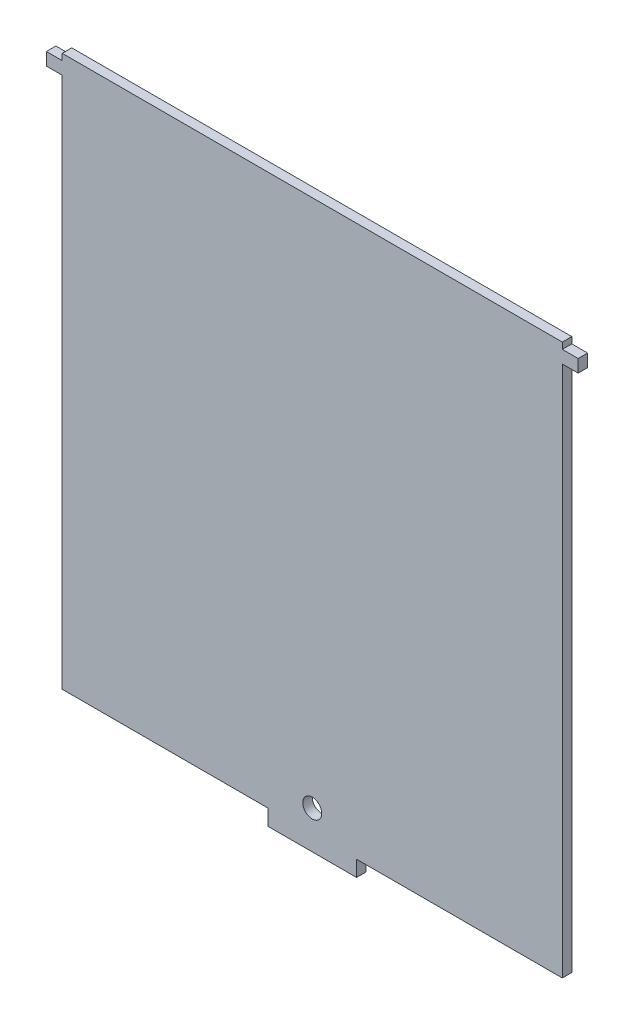
SolidWorks part; units mm, degrees
ref_plane "Front Plane" through (0, 0, 0) normal (0, 0, 1) x (1, 0, 0)
ref_plane "Top Plane" through (0, 0, 0) normal (0, 1, 0) x (1, 0, 0)
ref_plane "Right Plane" through (0, 0, 0) normal (1, 0, 0) x (0, 0, -1)
sketch "Sketch2" plane through (0, 0, 0) normal (0, 0, 1) x (1, 0, 0)
  line L0 (10.4351, -72.3206) -> (75.4351, -72.3206)
  line L2 (-82.5649, 95.6794) -> (-82.5649, -72.3206)
  line L3 (-82.5649, -72.3206) -> (-17.5649, -72.3206)
  line L4 (75.4351, 95.6794) -> (75.4351, -72.3206)
  line L5 (75.4351, 99.6794) -> (80.4351, 99.6794)
  line L7 (75.4351, 95.6794) -> (80.4351, 95.6794)
  line L8 (80.4351, 99.6794) -> (80.4351, 95.6794)
  line L9 (-82.5649, 99.6794) -> (-87.5649, 99.6794)
  line L11 (-82.5649, 95.6794) -> (-87.5649, 95.6794)
  line L12 (-87.5649, 99.6794) -> (-87.5649, 95.6794)
  line L14 (-17.5649, -72.3206) -> (-17.5649, -77.3206)
  line L15 (-17.5649, -77.3206) -> (10.4351, -77.3206)
  line L16 (10.4351, -72.3206) -> (10.4351, -77.3206)
  line L19 (-82.5649, 99.6794) -> (-82.5649, 101.6794)
  line L20 (-82.5649, 101.6794) -> (75.4351, 101.6794)
  line L21 (75.4351, 99.6794) -> (75.4351, 101.6794)
  circle A0 centre (-3.5649, -65.3206) radius 3
  dimension "D10" = 14
  dimension "D1" = 158
  dimension "D2" = 5
  dimension "D3" = 4
  dimension "D4" = 5
  dimension "D5" = 4
  dimension "D6" = 172
  dimension "D7" = 28
  dimension "D8" = 5
  dimension "D9" = 65
  dimension "D11" = 7
  dimension "D12" = 2
extrude "Boss-Extrude1" add sketch "Sketch2" along normal blind 3
